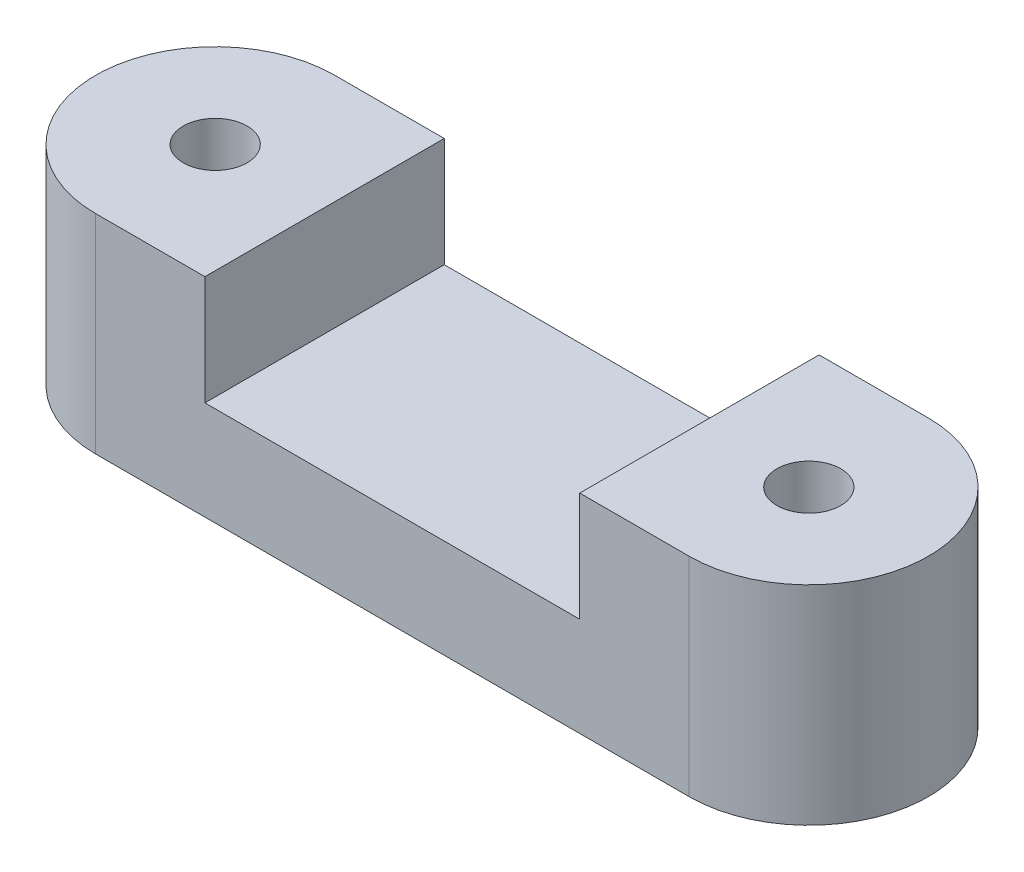
SolidWorks part; units mm, degrees
ref_plane "Front Plane" through (0, 0, 0) normal (0, 0, 1) x (1, 0, 0)
ref_plane "Top Plane" through (0, 0, 0) normal (0, 1, 0) x (1, 0, 0)
ref_plane "Right Plane" through (0, 0, 0) normal (1, 0, 0) x (0, 0, -1)
sketch "Sketch1" plane through (0, 0, 0) normal (0, 1, 0) x (1, 0, 0)
  line L0 (0, 0) -> (27.1526, 0) construction
  line L1 (0, 5.4737) -> (27.1526, 5.4737)
  line L2 (0, -5.4737) -> (27.1526, -5.4737)
  arc A0 (0, 5.4737) -> (0, -5.4737) centre (0, 0) ccw
  arc A1 (27.1526, -5.4737) -> (27.1526, 5.4737) centre (27.1526, 0) ccw
  circle A2 centre (0, 0) radius 1.4605
  circle A3 centre (27.1526, 0) radius 1.4605
  point P3 (13.5763, 0)
  dimension "D3" = 2.921
  dimension "D1" = 10.9474
  dimension "D2" = 27.1526
extrude "Boss-Extrude1" add sketch "Sketch1" along normal blind 9.525
sketch "Sketch2" plane through (0, 9.525, 0) normal (0, 1, 0) x (1, 0, 0)
  line L0 (-5.4737, 0) -> (32.6263, 0) construction
  line L1 (27.1526, 5.4737) -> (0, 5.4737) construction
  line L2 (5.0038, -5.4737) -> (22.1488, -5.4737)
  line L3 (5.0038, -5.4737) -> (5.0038, 5.4737)
  line L4 (5.0038, 5.4737) -> (22.1488, 5.4737)
  line L5 (22.1488, -5.4737) -> (22.1488, 5.4737)
  line L6 (5.0038, -5.4737) -> (22.1488, 5.4737) construction
  line L7 (5.0038, 5.4737) -> (22.1488, -5.4737) construction
  arc A0 (0, 5.4737) -> (0, -5.4737) centre (0, 0) ccw construction
  arc A1 (27.1526, -5.4737) -> (27.1526, 5.4737) centre (27.1526, 0) ccw construction
  point P8 (13.5763, 0)
  dimension "D1" = 17.145
extrude "Cut-Extrude1" cut sketch "Sketch2" against normal blind 5
ref_plane "Plane2" through (0, 0, 0) normal (0, 0, -1) x (-1, 0, 0)
ref_plane "Plane3" through (13.5763, 0, 0) normal (-1, 0, 0) x (0, 0, 1)
equation "\"D2@Sketch1\"=1.5in-\"D1@Sketch1\""
